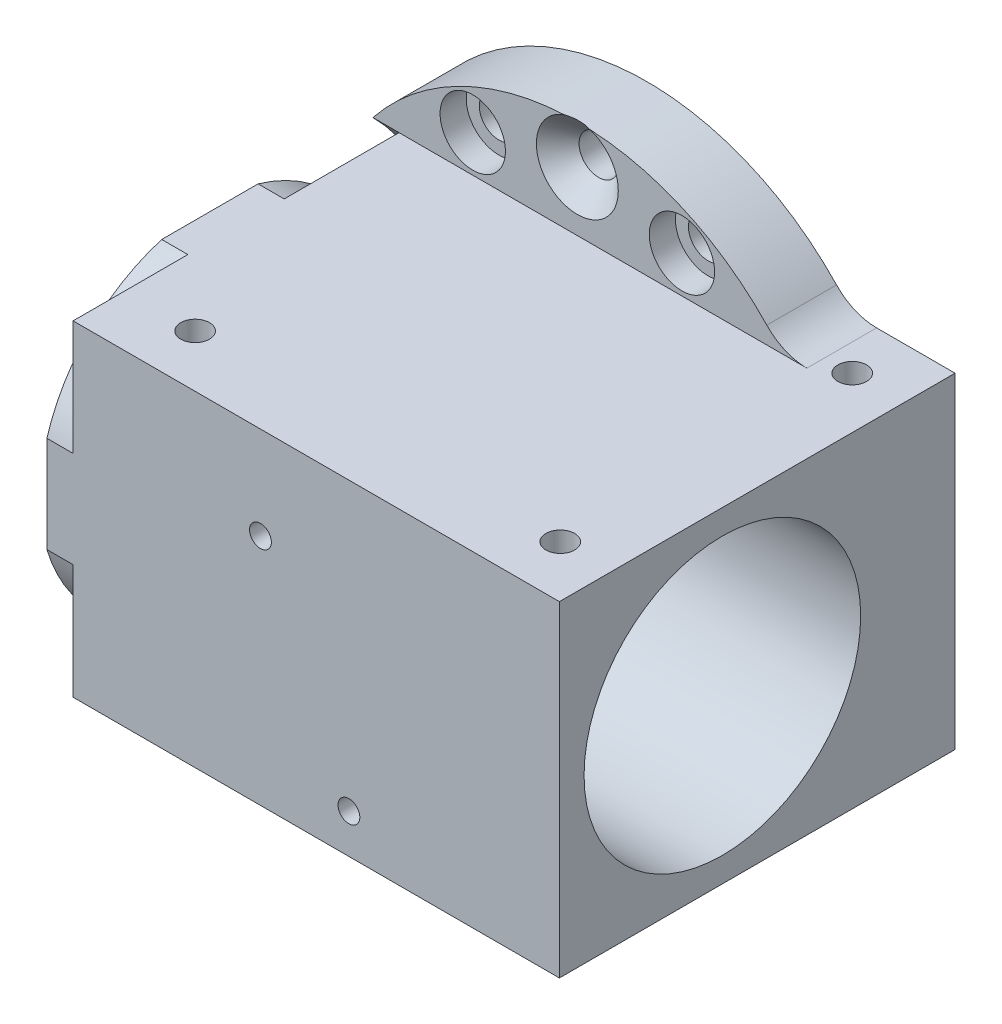
SolidWorks part; units mm, degrees
ref_plane "Front Plane" through (0, 0, 0) normal (0, 0, 1) x (1, 0, 0)
ref_plane "Top Plane" through (0, 0, 0) normal (0, 1, 0) x (1, 0, 0)
ref_plane "Right Plane" through (0, 0, 0) normal (1, 0, 0) x (0, 0, -1)
ref_plane "Plane1" through (0, 0, 8) normal (0, 0, 1) x (1, 0, 0)
sketch "Sketch1" plane through (0, 0, 8) normal (0, 0, 1) x (1, 0, 0)
  line L0 (-23.4587, 18.7) -> (-23.4587, -18.7)
  line L1 (23.4587, -18.7) -> (35.3413, -18.7)
  line L2 (35.3413, -18.7) -> (35.3413, 18.7)
  line L3 (35.3413, 18.7) -> (23.4587, 18.7)
  arc A0 (-23.4587, -18.7) -> (23.4587, -18.7) centre (0, 0) ccw
  arc A1 (23.4587, 18.7) -> (-23.4587, 18.7) centre (0, 0) ccw
extrude "Boss-Extrude1" add sketch "Sketch1" against normal blind 8
ref_plane "Plane2" through (-23.4587, 0, 0) normal (-1, 0, 0) x (0, -1, 0)
ref_plane "Plane3" through (-20.4587, 0, 0) normal (1, 0, 0) x (0, 0, -1)
sketch "Sketch3" plane through (-20.4587, 0, 0) normal (1, 0, 0) x (0, 0, -1)
  line L0 (-8, 18.7) -> (-8, -18.7)
  arc A0 (-8, -18.7) -> (-8, 18.7) centre (-26.7, 0) ccw
extrude "Cut-Extrude1" cut sketch "Sketch3" against normal up to surface up to plane "Plane2"
sketch "Sketch4" plane through (0, 0, 8) normal (0, 0, 1) x (1, 0, 0)
  line L0 (-20.4587, -18.7) -> (-20.4587, 18.7)
  line L1 (-20.4587, 18.7) -> (35.3413, 18.7)
  line L2 (35.3413, 18.7) -> (35.3413, -18.7)
  line L3 (35.3413, -18.7) -> (-20.4587, -18.7)
extrude "Boss-Extrude2" add sketch "Sketch4" along normal blind 37.4
sketch "Sketch5" plane through (-20.4587, 0, 0) normal (-1, 0, 0) x (0, 0, 1)
  line L0 (21.1719, 18.7) -> (45.4, 18.7)
  line L1 (45.4, 18.7) -> (45.4, -18.7)
  line L2 (45.4, -18.7) -> (21.1719, -18.7)
  arc A0 (21.1719, -18.7) -> (21.1719, 18.7) centre (26.7, 0) cw
extrude "Boss-Extrude3" add sketch "Sketch5" along normal blind 3
sketch "Sketch6" plane through (-23.4587, 0, 0) normal (-1, 0, 0) x (0, 0, 1)
  line L0 (45.4, -18.7) -> (45.4, -5.5281)
  line L1 (32.2281, -18.7) -> (45.4, -18.7)
  arc A0 (45.4, -5.5281) -> (32.2281, -18.7) centre (26.7, 0) cw
extrude "Cut-Extrude2" cut sketch "Sketch6" against normal blind 3
sketch "Sketch7" plane through (-23.4587, 0, 0) normal (-1, 0, 0) x (0, 0, 1)
  line L0 (45.4, 18.7) -> (32.2281, 18.7)
  line L1 (45.4, 5.5281) -> (45.4, 18.7)
  arc A0 (32.2281, 18.7) -> (45.4, 5.5281) centre (26.7, 0) cw
extrude "Cut-Extrude3" cut sketch "Sketch7" against normal blind 3
ref_plane "Plane4" through (0, 0, 26.7) normal (0, 0, 1) x (1, 0, 0)
sketch "Sketch8" plane through (0, 0, 26.7) normal (0, 0, 1) x (1, 0, 0)
  line L0 (-23.4587, 15.8686) -> (-23.4587, 0)
  line L1 (-23.4587, 0) -> (35.3413, 0)
  line L2 (35.3413, 0) -> (35.3413, 15.8687)
  line L3 (35.3413, 15.8687) -> (9.9413, 15.8687)
  line L4 (9.9413, 15.8687) -> (9.9413, 13.5)
  line L5 (9.9413, 13.5) -> (1.9413, 13.5)
  line L6 (1.9413, 13.5) -> (1.9413, 15.8686)
  line L7 (1.9413, 15.8686) -> (-23.4587, 15.8686)
  line L8 (-23.4587, 0) -> (35.3413, 0) construction
revolve "Cut-Revolve1" cut sketch "Sketch8" angle 360 about L8
hole_wizard "CSK for #8 Flat Head Machine Screw (100)1" positions "Sketch10" profile "Sketch9" countersink size "#8" standard "ANSI Inch"
sketch "Sketch10" plane through (0, 0, 8) normal (0, 0, 1) x (1, 0, 0)
  point P0 (0, 25.5)
  point P1 (0, -25.5)
sketch "Sketch9" plane through (0, 25.5, 8) normal (1, 0, 0) x (0, -1, 0)
  line L0 (0, 0) -> (0, 8)
  line L1 (0, 8) -> (2.25, 8)
  line L2 (2.25, 8) -> (2.25, 2.45)
  line L3 (2.25, 2.45) -> (4.7, 0)
  line L5 (4.7, 0) -> (0, 0)
  line L6 (-2.25, 2.45) -> (-4.7, 0) construction
  line L11 (0, -6.35) -> (0, 107.95) construction
  dimension "Thru Hole Dia." = 4.5
  dimension "Thru Hole Depth" = 8
  dimension "Near C'Sink Dia." = 9.4
  dimension "Near C'Sink Angle" = 90
hole_wizard "#4 Clearance Hole1" positions "Sketch12" profile "Sketch11" hole size "#4" standard "ANSI Inch"
sketch "Sketch12" plane through (0, -18.7, 0) normal (0, -1, 0) x (-1, 0, 0)
  point P0 (12.4587, -39.4)
  point P1 (-29.4413, -39.4)
  point P2 (-29.4413, -5.9)
sketch "Sketch11" plane through (-12.4587, -18.7, 39.4) normal (1, 0, 0) x (0, 0, -1)
  line L0 (0, 0) -> (0, 6)
  line L1 (0, 6) -> (1.65, 6)
  line L2 (1.65, 6) -> (1.65, 0)
  line L5 (1.65, 0) -> (0, 0)
  line L10 (0, 6) -> (-1.65, 6) construction
  line L11 (0, -6.35) -> (0, 107.95) construction
  dimension "Hole Dia." = 3.3
  dimension "Hole Depth" = 6
  dimension "Drill Angle" = 180
hole_wizard "CBORE for #8 Binding Head Machine Screw1" positions "Sketch14" profile "Sketch13" counterbore size "#8" standard "ANSI Inch"
sketch "Sketch14" plane through (0, 0, 8) normal (0, 0, 1) x (1, 0, 0)
  point P0 (12, 22.95)
  point P1 (-12, 22.95)
  point P2 (-12, -22.95)
  point P3 (12, -22.95)
sketch "Sketch13" plane through (12, 22.95, 8) normal (1, 0, 0) x (0, -1, 0)
  line L0 (0, 0) -> (0, 8)
  line L1 (0, 8) -> (2.25, 8)
  line L3 (2.25, 8) -> (2.25, 3)
  line L4 (2.25, 3) -> (3.75, 3)
  line L5 (3.75, 3) -> (3.75, 0)
  line L7 (3.75, 0) -> (0, 0)
  line L11 (0, -6.35) -> (0, 107.95) construction
  dimension "Thru Hole Dia." = 4.5
  dimension "Thru Hole Depth" = 8
  dimension "C'Bore Dia." = 7.5
  dimension "C'Bore Depth" = 3
hole_wizard "#2 Clearance Hole1" positions "Sketch16" profile "Sketch15" hole size "#2" standard "ANSI Inch"
sketch "Sketch16" plane through (0, 0, 45.4) normal (0, 0, 1) x (1, 0, 0)
  point P0 (-0.8087, 14.63)
sketch "Sketch15" plane through (-0.8087, 14.63, 45.4) normal (1, 0, 0) x (0, -1, 0)
  line L0 (0, 0) -> (0, 6)
  line L1 (0, 6) -> (1.25, 6)
  line L2 (1.25, 6) -> (1.25, 0)
  line L5 (1.25, 0) -> (0, 0)
  line L10 (0, 6) -> (-1.25, 6) construction
  line L11 (0, -6.35) -> (0, 107.95) construction
  dimension "Hole Dia." = 2.5
  dimension "Hole Depth" = 6
  dimension "Drill Angle" = 180
hole_wizard "#2 Clearance Hole2" positions "Sketch18" profile "Sketch17" hole size "#2" standard "ANSI Inch"
sketch "Sketch18" plane through (0, 0, 45.4) normal (0, 0, 1) x (1, 0, 0)
  point P0 (15.9651, -3.2)
sketch "Sketch17" plane through (15.9651, -3.2, 45.4) normal (1, 0, 0) x (0, -1, 0)
  line L0 (0, 0) -> (0, 3.1573)
  line L1 (0, 3.1573) -> (1.25, 3.1573)
  line L2 (1.25, 3.1573) -> (1.25, 0)
  line L5 (1.25, 0) -> (0, 0)
  line L11 (0, -6.35) -> (0, 107.95) construction
  dimension "Thru Hole Dia." = 2.5
  dimension "Thru Hole Depth" = 3.1573
fillet "Fillet1" radius 6.35 1 edges at (23.4587, 18.7, 4)
sketch "Sketch20" plane through (0, 0, 45.4) normal (0, 0, 1) x (1, 0, 0)
  line L0 (35.3413, 18.7) -> (-20.4587, 18.7) construction
  line L1 (-20.4587, -18.7) -> (35.3413, -18.7) construction
  line L2 (-23.4587, 18.7) -> (-23.4587, 5.5281) construction
  point P0 (1.0413, 8.0737)
  point P1 (11.1917, -14.199)
  dimension "D1" = 10.6263
  dimension "D2" = 4.501
  dimension "D3" = 24.4766
  dimension "D4" = 24.5
hole_wizard "M3x0.5 Tapped Hole1" positions "3DSketch1" profile "Sketch23" tap size "M3x0.5" standard "ANSI Metric"
sketch3d "3DSketch1"
  point P0 (1.0413, 8.0737, 45.4)
  point P3 (11.1917, -14.199, 45.4)
sketch "Sketch23" plane through (1.0413, 8.0737, 45.4) normal (1, 0, 0) x (0, -1, 0)
  line L0 (0, 0) -> (0, 4.7511)
  line L1 (0, 4.7511) -> (1.25, 4)
  line L2 (1.25, 4) -> (1.25, 0)
  line L5 (1.25, 0) -> (0, 0)
  line L10 (0, 4.7511) -> (-1.25, 4) construction
  line L11 (0, -6.35) -> (0, 107.95) construction
  dimension "Tap Drill Dia." = 2.5
  dimension "Tap Drill Depth" = 4
  dimension "Drill Angle" = 118
cosmetic thread "Hole Thread1" parameters "D1"=4, "D2"=3
cosmetic thread "Hole Thread2" parameters "D1"=4, "D2"=3
fillet "Fillet2" radius 6.35 1 edges at (23.4587, -18.7, 4)
sketch "草图1" plane through (0, 18.7, 0) normal (0, 1, 0) x (1, 0, 0)
  circle A0 centre (29.4413, -5.9) radius 1.65 construction
  circle A1 centre (29.4413, -5.9) radius 1.65
  circle A2 centre (-12.4587, -39.4) radius 1.65 construction
  circle A3 centre (29.4413, -39.4) radius 1.65 construction
  circle A4 centre (-12.4587, -39.4) radius 1.65
  circle A5 centre (29.4413, -39.4) radius 1.65
extrude "切除-拉伸1" cut sketch "草图1" against normal blind 6
sketch "草图2" plane through (0, -18.7, 0) normal (0, -1, 0) x (1, 0, 0)
  circle A0 centre (29.4413, 5.9) radius 1.65 construction
  circle A1 centre (29.4413, 39.4) radius 1.65 construction
  circle A2 centre (-12.4587, 39.4) radius 1.65 construction
  circle A3 centre (29.4413, 5.9) radius 1.65
  circle A4 centre (29.4413, 39.4) radius 1.65
  circle A5 centre (-12.4587, 39.4) radius 1.65
extrude "凸台-拉伸1" add sketch "草图2" against normal blind 6
